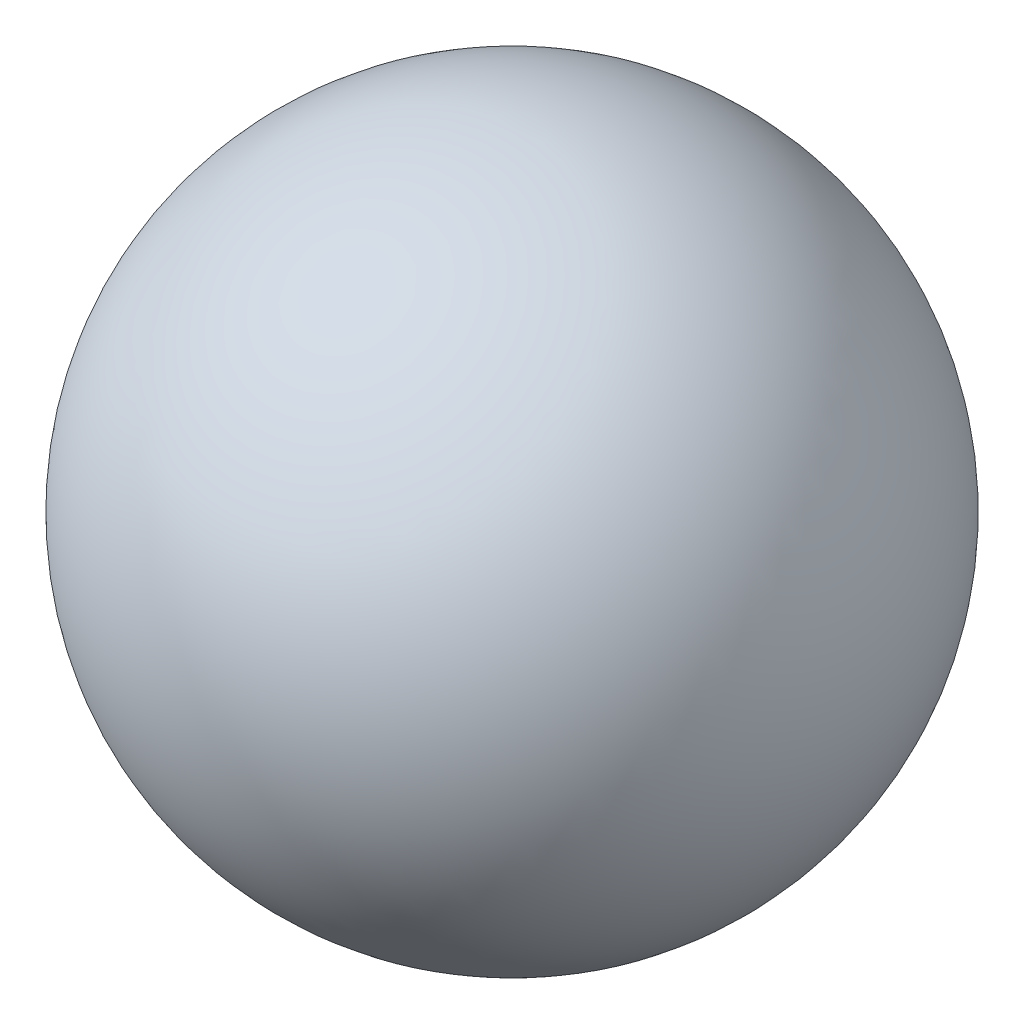
SolidWorks part; units mm, degrees
ref_plane "Front Plane" through (0, 0, 0) normal (0, 0, 1) x (1, 0, 0)
ref_plane "Top Plane" through (0, 0, 0) normal (0, 1, 0) x (1, 0, 0)
ref_plane "Right Plane" through (0, 0, 0) normal (1, 0, 0) x (0, 0, -1)
sketch "Sketch6" plane through (0, 0, 0) normal (0, 0, 1) x (1, 0, 0)
  line L0 (18.6449, 40.933) -> (18.6449, -84.2234)
  arc A0 (18.6449, -84.2234) -> (18.6449, 40.933) centre (18.6449, -21.6452) ccw
  dimension "D2" = 62.5782
  dimension "D1" = 125.1564
revolve "Revolve7" add sketch "Sketch6" angle 360 about L0
